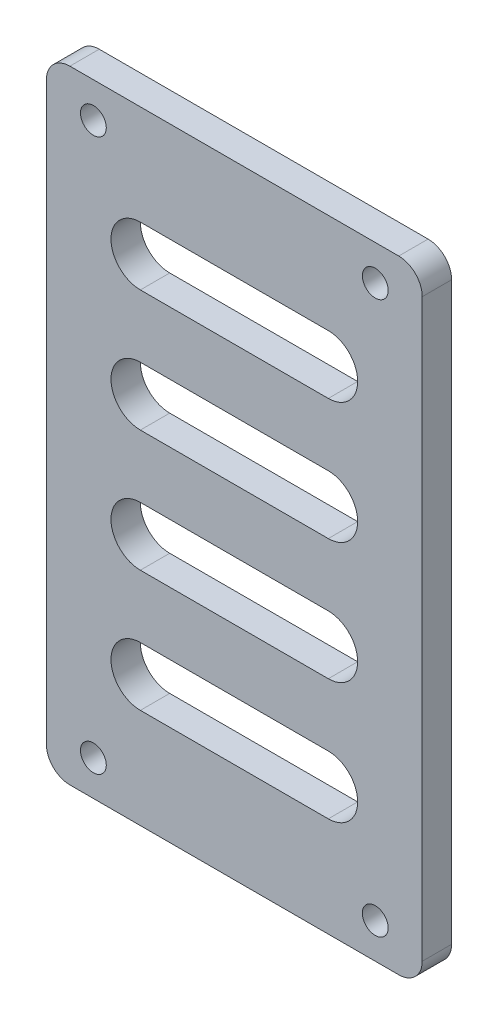
SolidWorks part; units mm, degrees
material "Acrylic (Medium-high impact)"
ref_plane "Front Plane" through (0, 0, 0) normal (0, 0, 1) x (1, 0, 0)
ref_plane "Top Plane" through (0, 0, 0) normal (0, 1, 0) x (1, 0, 0)
ref_plane "Right Plane" through (0, 0, 0) normal (1, 0, 0) x (0, 0, -1)
sketch "Sketch1" plane through (0, 0, 0) normal (0, 0, 1) x (1, 0, 0)
  line L0 (0, 0) -> (0, 50000) construction
  line L1 (-16, -26.5) -> (16, -26.5)
  line L2 (-16, -26.5) -> (-16, 26.5)
  line L3 (-16, 26.5) -> (16, 26.5)
  line L4 (16, -26.5) -> (16, 26.5)
  line L5 (-12, 23.5) -> (12, 23.5) construction
  line L6 (-12, 23.5) -> (-12, -23.5) construction
  line L7 (-14.5958, 21) -> (14.5958, 21) construction
  line L8 (-14.5958, 21) -> (-14.5958, 26) construction
  line L9 (-14.5958, 26) -> (14.5958, 26) construction
  line L10 (14.5958, 21) -> (14.5958, 26) construction
  line L11 (-14.5958, 21) -> (14.5958, 26) construction
  line L12 (-14.5958, 26) -> (14.5958, 21) construction
  circle A0 centre (0, 0) radius 9.5 construction
  circle A5 centre (-12, 23.5) radius 1.1
  circle A6 centre (12, -23.5) radius 1.1
  circle A7 centre (12, 23.5) radius 1.1
  circle A8 centre (-12, -23.5) radius 1.1
  circle A10 centre (0, 0) radius 18.75 construction
  point P0 (0, 0)
  point P19 (0, 0)
  point P25 (0, 23.5)
  point P30 (0, 23.5)
  point P33 (-12, 0)
  point P36 (16, 0)
  dimension "D1" = 19
  dimension "D4" = 2.2
  dimension "D10" = 37.5
  dimension "D5" = 24
  dimension "D6" = 47
  dimension "D7" = 53
  dimension "D9" = 5
  dimension "D11" = 32
extrude "Boss-Extrude1" add sketch "Sketch1" along normal blind 2.5
sketch "Sketch4" plane through (0, 0, 2.5) normal (0, 0, 1) x (1, 0, 0)
  line L0 (-8, 15.5) -> (8, 15.5) construction
  line L1 (-8, 18) -> (8, 18)
  line L2 (-8, 13) -> (8, 13)
  line L3 (16, 26.5) -> (-16, 26.5) construction
  line L4 (-8, 2.6667) -> (8, 2.6667)
  line L5 (-8, 7.6667) -> (8, 7.6667)
  line L6 (-8, 5.1667) -> (8, 5.1667) construction
  line L7 (-8, -7.6667) -> (8, -7.6667)
  line L8 (-8, -2.6667) -> (8, -2.6667)
  line L9 (-8, -5.1667) -> (8, -5.1667) construction
  line L10 (-8, -18) -> (8, -18)
  line L11 (-8, -13) -> (8, -13)
  line L12 (-8, -15.5) -> (8, -15.5) construction
  line L14 (-16, -26.5) -> (16, -26.5) construction
  arc A0 (-8, 18) -> (-8, 13) centre (-8, 15.5) ccw
  arc A1 (8, 13) -> (8, 18) centre (8, 15.5) ccw
  arc A2 (-8, 7.6667) -> (-8, 2.6667) centre (-8, 5.1667) ccw
  arc A3 (8, 2.6667) -> (8, 7.6667) centre (8, 5.1667) ccw
  arc A4 (-8, -2.6667) -> (-8, -7.6667) centre (-8, -5.1667) ccw
  arc A5 (8, -7.6667) -> (8, -2.6667) centre (8, -5.1667) ccw
  arc A6 (-8, -13) -> (-8, -18) centre (-8, -15.5) ccw
  arc A7 (8, -18) -> (8, -13) centre (8, -15.5) ccw
  point P2 (0, 15.5)
  point P13 (0, 5.1667)
  point P20 (0, -5.1667)
  point P27 (0, -15.5)
  dimension "D2" = 2.5
  dimension "D1" = 16
  dimension "D3" = 11
  dimension "D5" = 11
  dimension "D4" = 4
extrude "Cut-Extrude2" cut sketch "Sketch4" against normal through all
fillet "Fillet1" radius 2 4 edges at (-16, -26.5, 1.25) (16, -26.5, 1.25) (16, 26.5, 1.25) (-16, 26.5, 1.25)
